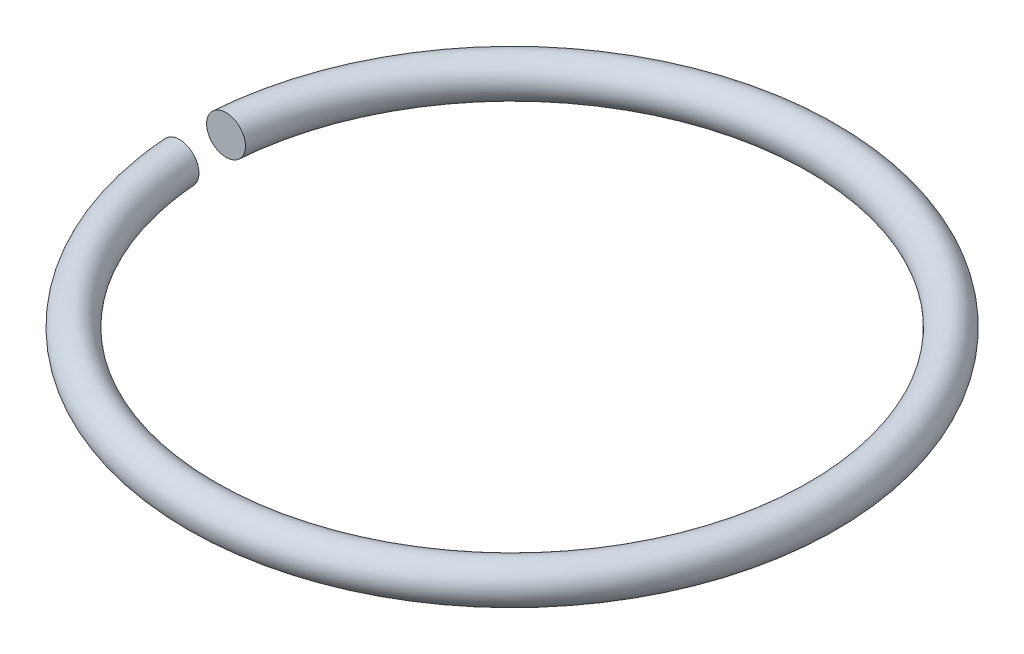
SolidWorks part; units mm, degrees
material "AISI 304"
ref_plane "Спереди" through (0, 0, 0) normal (0, 0, 1) x (1, 0, 0)
ref_plane "Сверху" through (0, 0, 0) normal (0, 1, 0) x (1, 0, 0)
ref_plane "Справа" through (0, 0, 0) normal (1, 0, 0) x (0, 0, -1)
sketch "Эскиз1" plane through (0, 0, 0) normal (0, 0, 1) x (1, 0, 0)
  line L0 (0, 0) -> (0, 42.813) construction
  circle A0 centre (-20, 1.25) radius 1.25
  dimension "D1" = 2.5
  dimension "D2" = 20
  dimension "D3" = 1.25
revolve "Повернуть1" add sketch "Эскиз1" angle 360 about L0
sketch "Эскиз2" plane through (0, 0, 0) normal (0, 1, 0) x (1, 0, 0)
  line L0 (0, 0) -> (-29.3009, 0) construction
  line L1 (-24.8398, 1.5) -> (-16.0773, 1.5)
  line L2 (-24.8398, 1.5) -> (-24.8398, -1.5)
  line L3 (-24.8398, -1.5) -> (-16.0773, -1.5)
  line L4 (-16.0773, 1.5) -> (-16.0773, -1.5)
  dimension "D1" = 3
  dimension "D2" = 1.5
extrude "Вырез-Вытянуть1" cut sketch "Эскиз2" along normal through all
ref_plane "Плоскость1" through (0, 0, 0) normal (0, -1, 0) x (-1, 0, 0)
